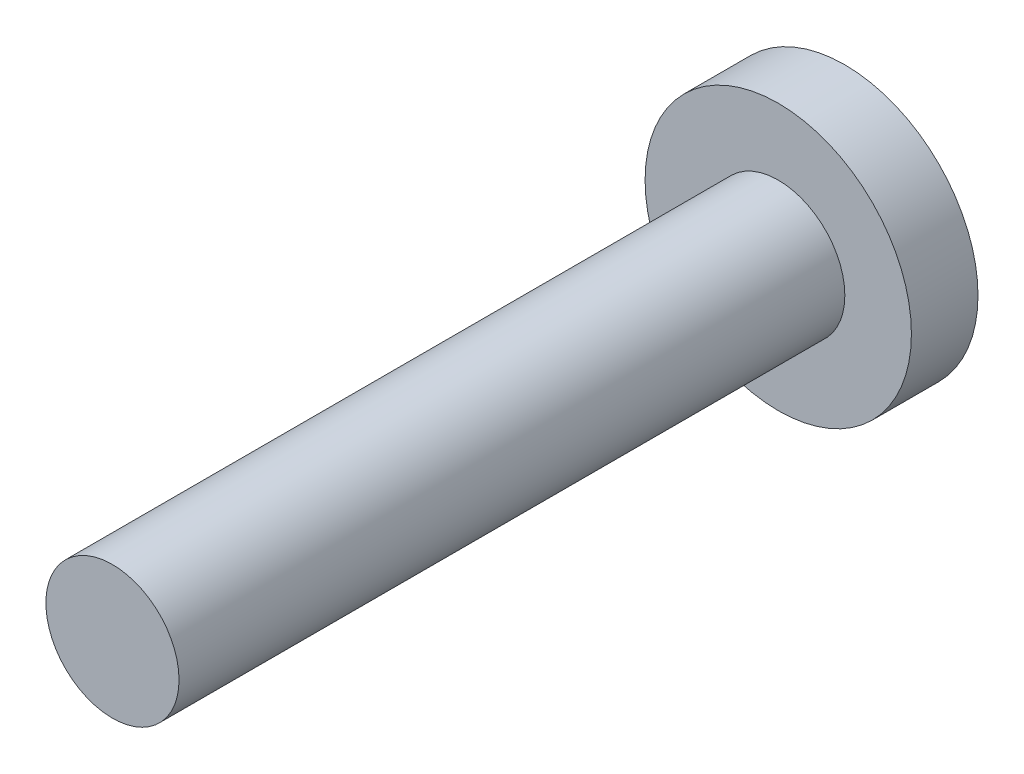
SolidWorks part; units mm, degrees
ref_plane "Front Plane" through (0, 0, 0) normal (0, 0, 1) x (1, 0, 0)
ref_plane "Top Plane" through (0, 0, 0) normal (0, 1, 0) x (1, 0, 0)
ref_plane "Right Plane" through (0, 0, 0) normal (1, 0, 0) x (0, 0, -1)
sketch "Sketch1" plane through (0, 0, 0) normal (0, 0, 1) x (1, 0, 0)
  circle A0 centre (0, 0) radius 5
  dimension "D1" = 10
extrude "Boss-Extrude1" add sketch "Sketch1" along normal blind 2.5
sketch "Sketch2" plane through (0, 0, 2.5) normal (0, 0, 1) x (1, 0, 0)
  circle A0 centre (0, 0) radius 2.5
  dimension "D1" = 5
extrude "Boss-Extrude2" add sketch "Sketch2" along normal blind 25
